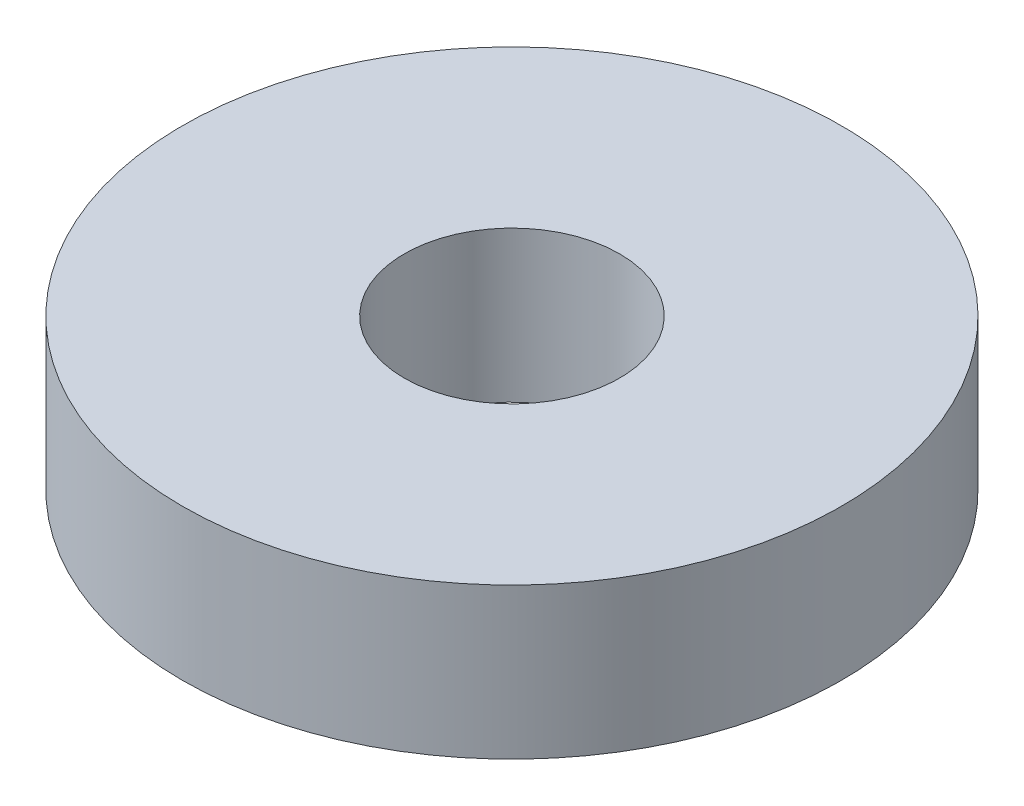
SolidWorks part; units mm, degrees
ref_plane "Front Plane" through (0, 0, 0) normal (0, 0, 1) x (1, 0, 0)
ref_plane "Top Plane" through (0, 0, 0) normal (0, 1, 0) x (1, 0, 0)
ref_plane "Right Plane" through (0, 0, 0) normal (1, 0, 0) x (0, 0, -1)
sketch "Sketch1" plane through (0, 0, 0) normal (0, 1, 0) x (1, 0, 0)
  circle A0 centre (0, 0) radius 7.65
  circle A1 centre (0, 0) radius 2.5
  dimension "D1" = 15.3
  dimension "D2" = 5
extrude "Boss-Extrude1" add sketch "Sketch1" along normal blind 3.5
